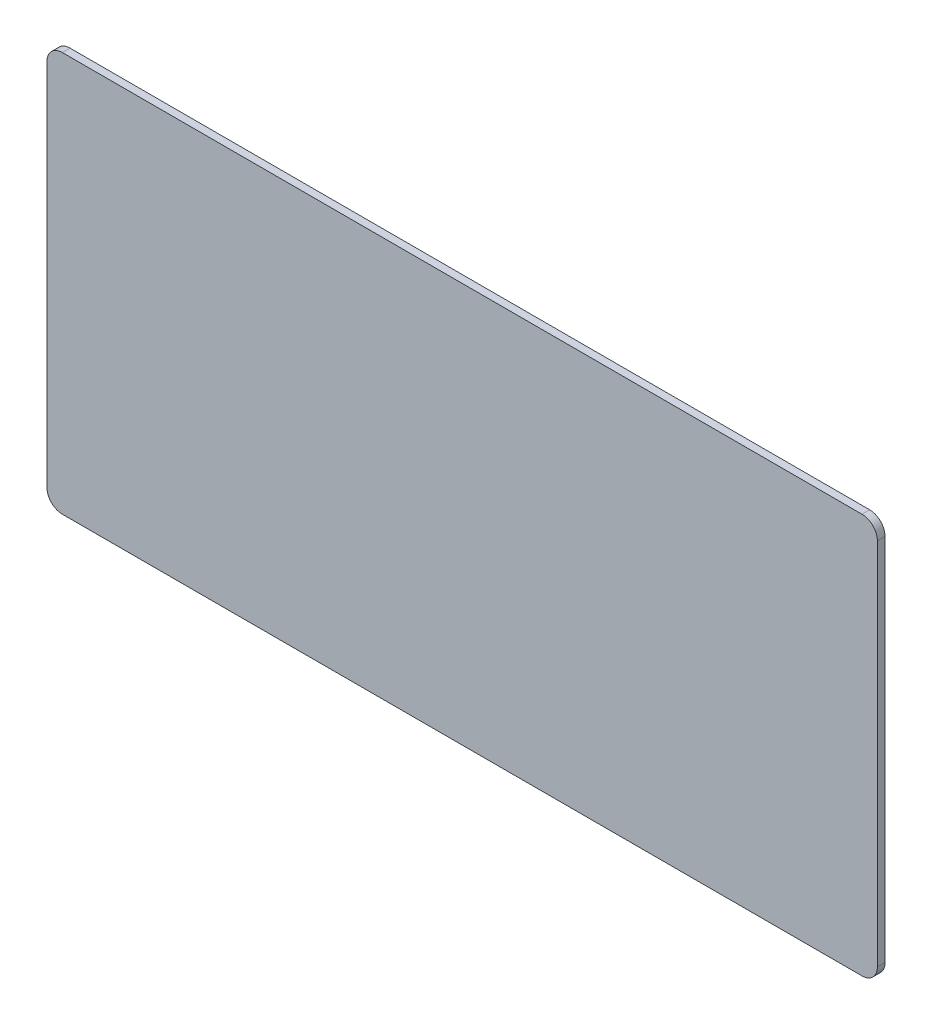
SolidWorks part; units mm, degrees
material "Thornel Mat VMA"
ref_plane "Front Plane" through (0, 0, 0) normal (0, 0, 1) x (1, 0, 0)
ref_plane "Top Plane" through (0, 0, 0) normal (0, 1, 0) x (1, 0, 0)
ref_plane "Right Plane" through (0, 0, 0) normal (1, 0, 0) x (0, 0, -1)
sketch "Sketch1" plane through (0, 0, 0) normal (0, 0, 1) x (1, 0, 0)
  line L1 (-270, -130) -> (270, -130)
  line L2 (-270, -130) -> (-270, 130)
  line L3 (-270, 130) -> (270, 130)
  line L4 (270, -130) -> (270, 130)
  line L5 (-270, -130) -> (270, 130) construction
  line L6 (-270, 130) -> (270, -130) construction
  point P0 (0, 0)
  dimension "D1" = 260
  dimension "D2" = 540
extrude "Boss-Extrude1" add sketch "Sketch1" along normal blind 5
fillet "Fillet1" radius 10 4 edges at (-270, -130, 2.5) (270, -130, 2.5) (270, 130, 2.5) (-270, 130, 2.5)
